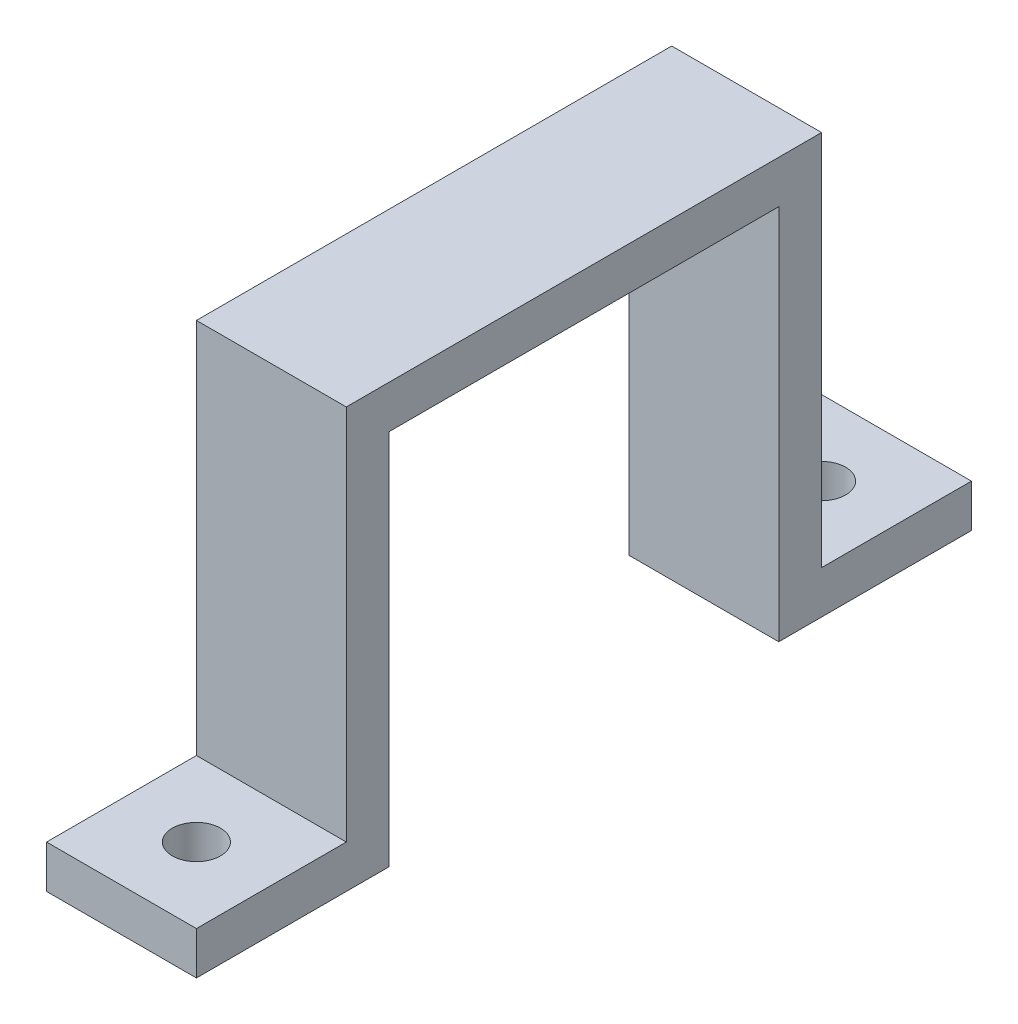
SolidWorks part; units mm, degrees
material "PETG"
ref_plane "Front Plane" through (0, 0, 0) normal (0, 0, 1) x (1, 0, 0)
ref_plane "Top Plane" through (0, 0, 0) normal (0, 1, 0) x (1, 0, 0)
ref_plane "Right Plane" through (0, 0, 0) normal (1, 0, 0) x (0, 0, -1)
other "Configuration Table"
sketch "Sketch1" plane through (0, 0, 0) normal (1, 0, 0) x (0, 0, -1)
  line L0 (-36.2, 0) -> (-18.2, 0)
  line L1 (-18.2, 0) -> (-18.2, 35.2)
  line L2 (-18.2, 35.2) -> (18.2, 35.2)
  line L3 (18.2, 35.2) -> (18.2, 0)
  line L4 (18.2, 0) -> (36.2, 0)
  line L5 (36.2, 0) -> (36.2, 4)
  line L6 (36.2, 4) -> (22.2, 4)
  line L7 (22.2, 4) -> (22.2, 39.2)
  line L8 (22.2, 39.2) -> (-22.2, 39.2)
  line L9 (-22.2, 39.2) -> (-22.2, 4)
  line L10 (-22.2, 4) -> (-36.2, 4)
  line L11 (-36.2, 4) -> (-36.2, 0)
extrude "Strap" add sketch "Sketch1" along normal mid plane 14
sketch "Sketch2" plane through (0, 0, 0) normal (0, 1, 0) x (1, 0, 0)
  circle A0 centre (0, 29.2) radius 2.25
  circle A1 centre (0, -29.2) radius 2.25
  dimension "D1" = 4.5
  dimension "D2" = 4.5
extrude "Ear_Holes_M4" cut sketch "Sketch2" along normal blind 5 from offset 0.5
equation "\"Jar_OD\"= 90  'ASSUMED - Part C fallback - jar outer diameter"
equation "\"Jar_H\"= 120  'ASSUMED - Part C fallback - jar height"
equation "\"Pump_L\"= 45  'ASSUMED - Part C fallback"
equation "\"Pump_W\"= 24  'ASSUMED - Part C fallback"
equation "\"Pump_H\"= 33  'ASSUMED - Part C fallback"
equation "\"Pump_Outlet_OD\"= 7.5  'ASSUMED - Part C fallback"
equation "\"Tube_OD\"= 8  'ASSUMED - Part C fallback"
equation "\"Tube_ID\"= 6  'ASSUMED - Part C fallback"
equation "\"TDS_Body_Dia\"= 12  'ASSUMED - Part C fallback"
equation "\"TDS_Wet_Len\"= 45  'ASSUMED - Part C fallback - length in water"
equation "\"DS_Tube_Dia\"= 6  'ASSUMED - Part C fallback"
equation "\"DS_Tube_Len\"= 50  'ASSUMED - Part C fallback"
equation "\"ORP_Body_Dia\"= 12  'ASSUMED - Part C fallback"
equation "\"ORP_Body_Len\"= 150  'ASSUMED - Part C fallback"
equation "\"ORP_Cap_Dia\"= 16  'ASSUMED - Part C fallback"
equation "\"Turb_W\"= 33  'ASSUMED - Part C fallback - head width"
equation "\"Turb_D\"= 28  'ASSUMED - Part C fallback - head depth"
equation "\"Turb_H\"= 30  'ASSUMED - Part C fallback - head height"
equation "\"Turb_Slot_W\"= 10  'ASSUMED - Part C fallback - slot width"
equation "\"Flow_L\"= 62  'ASSUMED - Part C fallback YF-S201"
equation "\"Flow_W\"= 36  'ASSUMED - Part C fallback"
equation "\"Flow_H\"= 35  'ASSUMED - Part C fallback"
equation "\"Thread_G12_OD\"= 20.955  'ASSUMED - Part C fallback thread G1/2 (major diameter)"
equation "\"Valve_L\"= 75  'ASSUMED - Part C fallback"
equation "\"Valve_W\"= 45  'ASSUMED - Part C fallback"
equation "\"Valve_H\"= 60  'ASSUMED - Part C fallback"
equation "\"Tee_L\"= 40  'ASSUMED - Part C fallback - overall length"
equation "\"Tee_Branch_L\"= 25  'ASSUMED - Part C fallback"
equation "\"Tee_OD\"= 12  'ASSUMED - Part C fallback"
equation "\"Cuv_W\"= 12.5  'ASSUMED - Part C fallback"
equation "\"Cuv_D\"= 12.5  'ASSUMED - Part C fallback"
equation "\"Cuv_H\"= 45  'ASSUMED - Part C fallback"
equation "\"LED_Board_L\"= 20  'ASSUMED - Part C fallback"
equation "\"LED_Board_W\"= 20  'ASSUMED - Part C fallback - LED at centre"
equation "\"GUVA_L\"= 20  'ASSUMED - Part C fallback"
equation "\"GUVA_W\"= 12  'ASSUMED - Part C fallback - sensor at centre"
equation "\"Reed_L\"= 27  'ASSUMED - Part C fallback MC-38 half"
equation "\"Reed_W\"= 14  'ASSUMED - Part C fallback"
equation "\"Reed_H\"= 8  'ASSUMED - Part C fallback"
equation "\"ESP_L\"= 51  'ASSUMED - Part C fallback"
equation "\"ESP_W\"= 28  'ASSUMED - Part C fallback"
equation "\"TFT_L\"= 58  'ASSUMED - Part C fallback - board"
equation "\"TFT_W\"= 35  'ASSUMED - Part C fallback - board"
equation "\"TFT_Win_L\"= 35  'ASSUMED - Part C fallback - visible window"
equation "\"TFT_Win_W\"= 28  'ASSUMED - Part C fallback - visible window"
equation "\"Relay_L\"= 50  'ASSUMED - Part C fallback"
equation "\"Relay_W\"= 26  'ASSUMED - Part C fallback"
equation "\"Relay_H\"= 19  'ASSUMED - Part C fallback"
equation "\"Mosfet_L\"= 34  'ASSUMED - Part C fallback"
equation "\"Mosfet_W\"= 17  'ASSUMED - Part C fallback"
equation "\"Mosfet_H\"= 12  'ASSUMED - Part C fallback"
equation "\"TDS_Board_L\"= 42  'ASSUMED - Part C fallback"
equation "\"TDS_Board_W\"= 32  'ASSUMED - Part C fallback"
equation "\"Turb_Board_L\"= 38  'ASSUMED - Part C fallback"
equation "\"Turb_Board_W\"= 28  'ASSUMED - Part C fallback"
equation "\"BNC_Thread_Dia\"= 9.5  'ASSUMED - Part C fallback"
equation "\"Plate_L\"= 420  'ASSUMED - Part C fallback"
equation "\"Plate_W\"= 297  'ASSUMED - Part C fallback"
equation "\"Plate_T\"= 6  'ASSUMED - Part C fallback"
equation "\"Probe_Clr\"= 0.3  'DESIGN VALUE - Part C rule 3 - printed probe hole = diameter + 0.3"
equation "\"Cuv_Clr\"= 0.2  'DESIGN VALUE - Part C rule 3 - cuvette pocket = size + 0.2"
equation "\"Label_H\"= 0.6  'DESIGN VALUE - Part D - raised label height"
